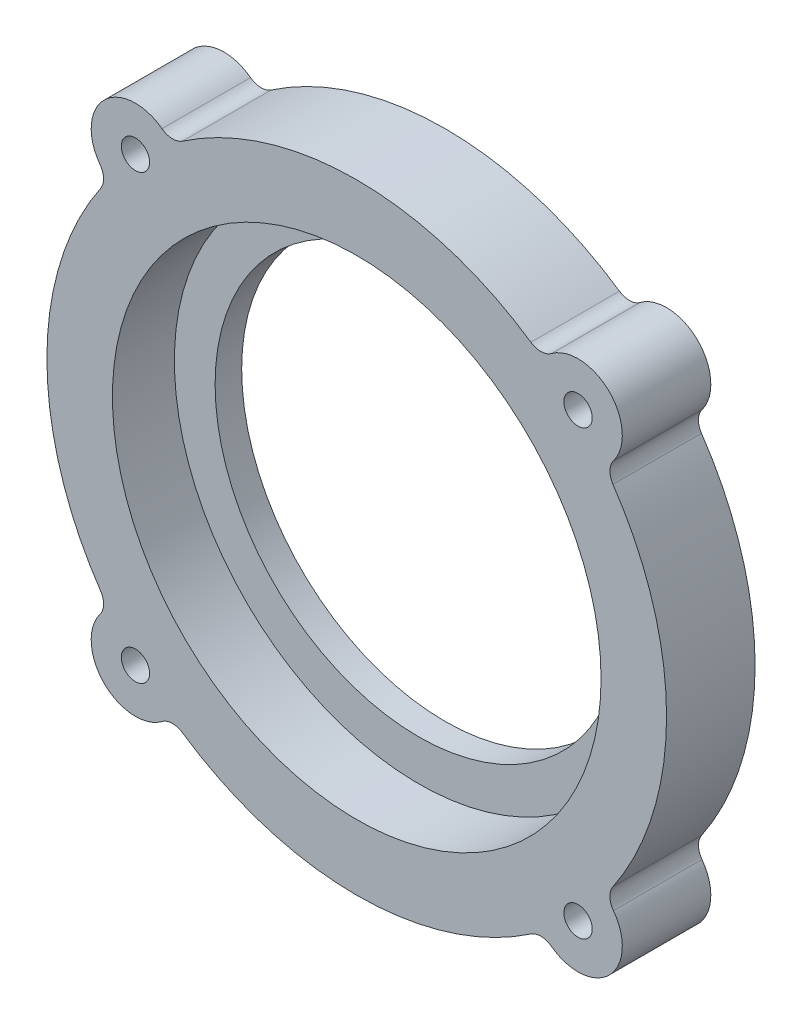
SolidWorks part; units mm, degrees
ref_plane "Front Plane" through (0, 0, 0) normal (0, 0, 1) x (1, 0, 0)
ref_plane "Top Plane" through (0, 0, 0) normal (0, 1, 0) x (1, 0, 0)
ref_plane "Right Plane" through (0, 0, 0) normal (1, 0, 0) x (0, 0, -1)
sketch "Sketch1" plane through (0, 0, 0) normal (0, 0, 1) x (1, 0, 0)
  circle A1 centre (0, 0) radius 23
  arc A2 (-28.9459, 19.6757) -> (-28.9459, -19.6757) centre (0, 0) ccw
  arc A3 (29, 22) -> (22, 29) centre (25, 25) ccw
  arc A5 (-29, -22) -> (-22, -29) centre (-25, -25) ccw
  arc A6 (22, -29) -> (29, -22) centre (25, -25) ccw
  circle A7 centre (-25, 25) radius 1.6
  circle A8 centre (25, 25) radius 1.6
  circle A9 centre (-25, -25) radius 1.6
  circle A10 centre (25, -25) radius 1.6
  arc A11 (-28.9459, -19.6757) -> (-29, -22) centre (-30.6, -20.8) cw
  arc A12 (-22, 29) -> (-29, 22) centre (-25, 25) ccw
  arc A13 (19.6757, 28.9459) -> (-19.6757, 28.9459) centre (0, 0) ccw
  arc A14 (-22, -29) -> (-19.6757, -28.9459) centre (-20.8, -30.6) cw
  arc A15 (-19.6757, -28.9459) -> (19.6757, -28.9459) centre (0, 0) ccw
  arc A16 (28.9459, -19.6757) -> (28.9459, 19.6757) centre (0, 0) ccw
  arc A17 (19.6757, -28.9459) -> (22, -29) centre (20.8, -30.6) cw
  arc A18 (29, -22) -> (28.9459, -19.6757) centre (30.6, -20.8) cw
  arc A19 (28.9459, 19.6757) -> (29, 22) centre (30.6, 20.8) cw
  arc A20 (22, 29) -> (19.6757, 28.9459) centre (20.8, 30.6) cw
  arc A21 (-28.9459, 19.6757) -> (-29, 22) centre (-30.6, 20.8) ccw
  arc A22 (-19.6757, 28.9459) -> (-22, 29) centre (-20.8, 30.6) cw
  point P20 (-21, -28)
  point P27 (28, -21)
  point P33 (21, 28)
  dimension "D1" = 46
  dimension "D5" = 70
  dimension "D6" = 3.2
  dimension "D7" = 3.2
  dimension "D8" = 3.2
  dimension "D9" = 3.2
  dimension "D10" = 10
  dimension "D11" = 50
  dimension "D12" = 10
  dimension "D13" = 10
  dimension "D14" = 5
  dimension "D15" = 2
  dimension "D2" = 50
  dimension "D3" = 50
  dimension "D4" = 50
extrude "Boss-Extrude1" add sketch "Sketch1" along normal blind 10
sketch "Sketch2" plane through (0, 0, 10) normal (0, 0, 1) x (1, 0, 0)
  circle A0 centre (0, 0) radius 27.6
  dimension "D1" = 55.2
extrude "Cut-Extrude1" cut sketch "Sketch2" against normal blind 7
